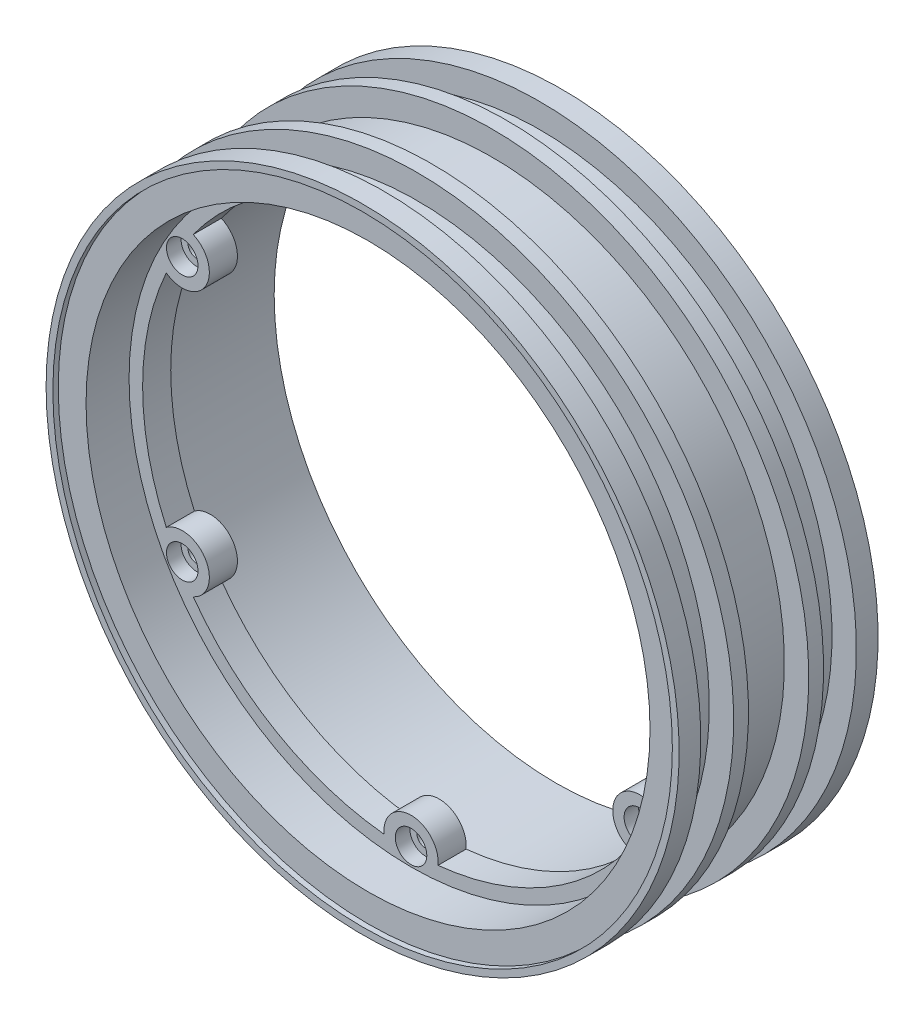
SolidWorks part; units mm, degrees
ref_plane "Piano frontale" through (0, 0, 0) normal (0, 0, 1) x (1, 0, 0)
ref_plane "Piano superiore" through (0, 0, 0) normal (0, 1, 0) x (1, 0, 0)
ref_plane "Piano destro" through (0, 0, 0) normal (1, 0, 0) x (0, 0, -1)
sketch "Schizzo1" plane through (0, 0, 0) normal (1, 0, 0) x (0, 0, -1)
  line L0 (0, 0) -> (0, 41.625) construction
  line L1 (-13.885, 41.625) -> (13.885, 41.625)
  line L2 (13.885, 41.625) -> (13.885, 45.725)
  line L3 (13.885, 45.725) -> (14.685, 45.725)
  line L4 (14.685, 45.725) -> (14.685, 46.725)
  line L5 (14.685, 46.725) -> (11.485, 46.725)
  line L6 (11.485, 46.725) -> (11.485, 43.125)
  line L7 (11.485, 43.125) -> (6.635, 43.125)
  line L8 (6.635, 43.125) -> (6.635, 46.725)
  line L9 (6.635, 46.725) -> (4.45, 46.725)
  line L10 (4.45, 46.725) -> (4.45, 43.125)
  line L11 (4.45, 43.125) -> (-4.45, 43.125)
  line L12 (0, 41.625) -> (0, 48.0242) construction
  line L13 (-4.45, 46.725) -> (-4.45, 43.125)
  line L14 (-6.635, 46.725) -> (-4.45, 46.725)
  line L15 (-6.635, 43.125) -> (-6.635, 46.725)
  line L16 (-11.485, 43.125) -> (-6.635, 43.125)
  line L17 (-11.485, 46.725) -> (-11.485, 43.125)
  line L18 (-14.685, 46.725) -> (-11.485, 46.725)
  line L19 (-14.685, 45.725) -> (-14.685, 46.725)
  line L20 (-13.885, 45.725) -> (-14.685, 45.725)
  line L21 (-13.885, 41.625) -> (-13.885, 45.725)
  line L22 (0, 0) -> (-35.9584, 0) construction
  point P16 (0, 43.125)
  dimension "D1" = 29.37
  dimension "D2" = 0.8
  dimension "D3" = 4.85
  dimension "D4" = 8.9
  dimension "D5" = 3.6
  dimension "D6" = 3.2
  dimension "D7" = 5.1
  dimension "D8" = 1
  dimension "D9" = 46.725
revolve "Rivoluzione1" add sketch "Schizzo1" angle 360 about L22
ref_plane "Piano1" through (0, 0, 3.385) normal (0, 0, 1) x (1, 0, 0)
sketch "Schizzo2" plane through (0, 0, 3.385) normal (0, 0, 1) x (1, 0, 0)
  circle A0 centre (0, 0) radius 41.625 construction
  circle A1 centre (0, 0) radius 41.625
  arc A2 (-36.1316, 16.2679) -> (-36.1316, -16.2679) centre (0, 0) ccw
  circle A3 centre (0, 0) radius 39 construction
  circle A4 centre (0, 39) radius 1.3
  arc A5 (-3.9774, 39.4249) -> (3.9774, 39.4249) centre (0, 39) ccw
  arc A6 (36.1316, -16.2679) -> (36.1316, 16.2679) centre (0, 0) ccw
  circle A7 centre (33.775, 19.5) radius 1.3
  arc A8 (36.1316, -16.2679) -> (32.1543, -23.1569) centre (33.775, -19.5) ccw
  circle A9 centre (33.775, -19.5) radius 1.3
  arc A10 (3.9774, -39.4249) -> (-3.9774, -39.4249) centre (0, -39) ccw
  circle A11 centre (0, -39) radius 1.3
  arc A12 (-32.1543, -23.1569) -> (-36.1316, -16.2679) centre (-33.775, -19.5) ccw
  circle A13 centre (-33.775, -19.5) radius 1.3
  arc A14 (-36.1316, 16.2679) -> (-32.1543, 23.1569) centre (-33.775, 19.5) ccw
  circle A15 centre (-33.775, 19.5) radius 1.3
  circle A16 centre (0, 0) radius 39.625 construction
  arc A17 (32.1543, 23.1569) -> (36.1316, 16.2679) centre (33.775, 19.5) ccw
  arc A18 (-3.9774, 39.4249) -> (-32.1543, 23.1569) centre (0, 0) ccw
  arc A19 (37.5051, 18.0557) -> (34.3892, 23.4526) centre (33.775, 19.5) ccw [skipped]
  arc A20 (32.1543, 23.1569) -> (3.9774, 39.4249) centre (0, 0) ccw
  arc A21 (3.9774, -39.4249) -> (32.1543, -23.1569) centre (0, 0) ccw
  arc A22 (-32.1543, -23.1569) -> (-3.9774, -39.4249) centre (0, 0) ccw
  point P27 (0, 0)
  dimension "D2" = 78
  dimension "D3" = 2.6
  dimension "D4" = 8
  dimension "D1" = 2
  dimension "D5" = 6
extrude "Estrusione-Estrusione1" add sketch "Schizzo2" along normal blind 4.15
sketch "Schizzo3" plane through (0, 0, 7.535) normal (0, 0, 1) x (1, 0, 0)
  circle A0 centre (-33.775, -19.5) radius 2.325
  circle A1 centre (-33.775, 19.5) radius 2.325
  circle A2 centre (0, 39) radius 2.325
  circle A3 centre (33.775, 19.5) radius 2.325
  circle A4 centre (33.775, -19.5) radius 2.325
  circle A5 centre (0, -39) radius 2.325
  point P16 (0, 0)
  dimension "D1" = 4.65
  dimension "D2" = 6
extrude "Taglio-Estrusione1" cut sketch "Schizzo3" against normal blind 2.15
